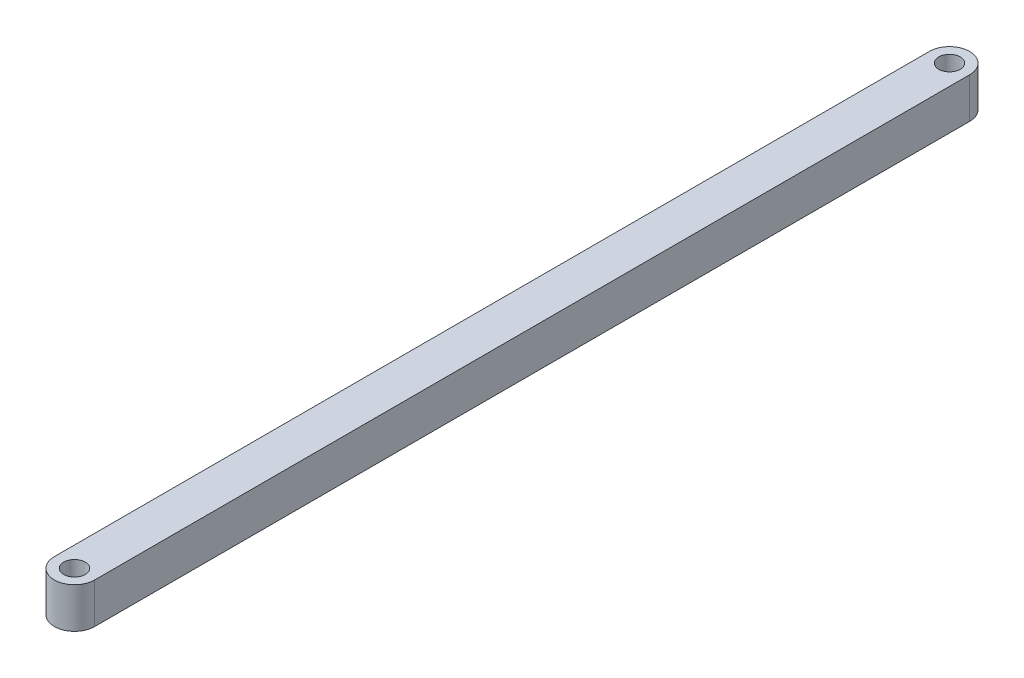
SolidWorks part; units mm, degrees
ref_plane "前视基准面" through (0, 0, 0) normal (0, 0, 1) x (1, 0, 0)
ref_plane "上视基准面" through (0, 0, 0) normal (0, 1, 0) x (1, 0, 0)
ref_plane "右视基准面" through (0, 0, 0) normal (1, 0, 0) x (0, 0, -1)
sketch "草图1" plane through (0, 0, 0) normal (0, 1, 0) x (1, 0, 0)
  line L0 (0, -64.9963) -> (0, 64.9963) construction
  line L1 (-3, -64.9963) -> (-3, 64.9963)
  line L2 (3, -64.9963) -> (3, 64.9963)
  arc A0 (-3, -64.9963) -> (3, -64.9963) centre (0, -64.9963) ccw
  arc A1 (3, 64.9963) -> (-3, 64.9963) centre (0, 64.9963) ccw
  circle A2 centre (0, 64.9963) radius 1.6
  circle A3 centre (0, -64.9963) radius 1.6
  point P2 (0, 0)
extrude "凸台-拉伸1" add sketch "草图1" along normal blind 6
